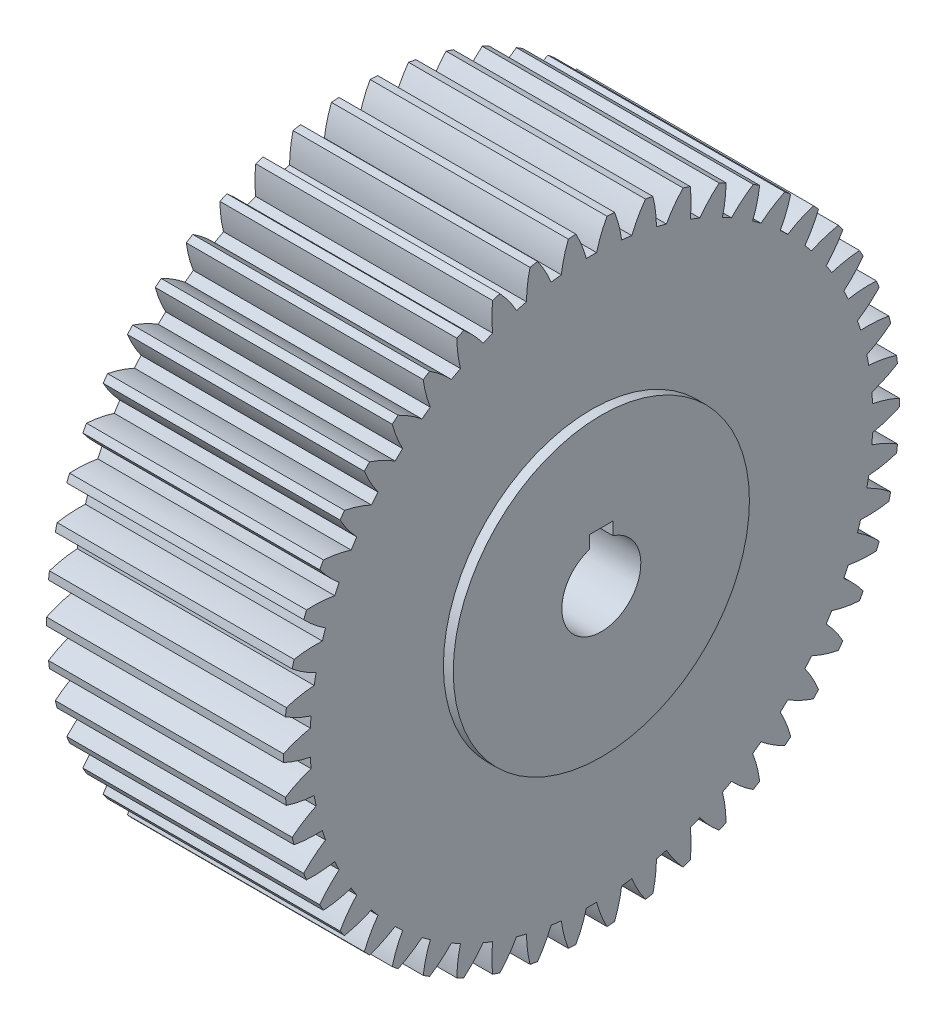
SolidWorks part; units mm, degrees
ref_plane "Plane1" through (0, 0, 0) normal (0, 0, 1) x (1, 0, 0)
ref_plane "Plane2" through (0, 0, 0) normal (0, 1, 0) x (1, 0, 0)
ref_plane "Plane3" through (0, 0, 0) normal (1, 0, 0) x (0, 0, -1)
other "Configuration Table"
sketch "HoldingSke" plane through (0, 0, 0) normal (0, 1, 0) x (1, 0, 0)
  line L0 (0, 0) -> (0.2143, -0.2553)
  line L1 (-15, 0) -> (100, 0) construction
  line L2 (0, 0) -> (-2.1039, 2.3779)
  line L3 (0, 0) -> (-11.863, 4.5341)
  line L4 (0, 0) -> (5.5511, 6.6156)
  line L5 (0, 0) -> (-60.9019, -22.7146)
  line L6 (0, 0) -> (-49.7378, -33.5582)
  line L7 (-2.1039, 2.3779) -> (11.8873, 65.8543)
  line L8 (-76.2, 54.61) -> (-73.4, 54.61)
  line L9 (-71.009, 38.7566) -> (-53.1078, 45.2721)
  line L10 (-76.2, 71.12) -> (104.1128, 71.12)
  line L11 (0, 0) -> (-60, 0)
  line L12 (-76.2, 101.6) -> (-76.093, 101.6)
  line L13 (24.9733, 27.94) -> (52.9518, 28.4284)
  line L14 (24.9733, 27.94) -> (24.9743, 27.94)
  line L15 (24.9733, 27.94) -> (100.4006, 29.5858)
  line L16 (-63.627, -3) -> (-12.827, -3)
  circle A0 centre (0, 0) radius 10
  circle A1 centre (0, 0) radius 37.5
  circle A2 centre (0, 0) radius 37.5
  circle A3 centre (0, 0) radius 10
  dimension "MHD" = 75
  dimension "Hub_dia" = 75
  dimension "Bore" = 20
  dimension "MBD" = 20
  dimension "Num_teeth" = 50
  dimension "Pitch" = 0.3333
  dimension "Overall_len" = 65
  dimension "Show_teeth" = 50
  dimension "Thickness" = 60
  dimension "OAL" = 65.0001
  dimension "T_dim" = 2.8
  dimension "Ap" = 20
  dimension "H" = 19.05
  dimension "Pitch_radius" = 180.3128
  dimension "Width" = 60
  dimension "Backlash" = 0.107
  dimension "Addendum_fac" = 1
  dimension "Dedendum_fac" = 1.25
  dimension "Clearance_fac" = 0.25
  dimension "Dedendum_add" = 0.001
  dimension "Module" = 3
sketch "BasProSke" plane through (0, 0, 0) normal (0, 1, 0) x (1, 0, 0)
  line L0 (-10, 0) -> (60, 0) construction
  line L1 (0, 0) -> (0, 78)
  line L2 (0, 0) -> (60, 0)
  line L3 (60, 0) -> (60, 78)
  line L4 (60, 78) -> (0, 78)
  dimension "Thickness" = 60
  dimension "Diameter" = 156
revolve "Base-Revolve" add sketch "BasProSke" angle 360 about L0
sketch "TooCutSke" plane through (0, 0, 0) normal (1, 0, 0) x (0, 0, -1)
  line L1 (0, 0) -> (0, 107) construction
  line L2 (0, 0) -> (-2.543, 74.9569) construction
  line L3 (0, 0) -> (-9.4146, 149.6414) construction
  line L4 (-2.543, 74.9569) -> (-4.7073, 74.8207) construction
  arc A0 (1.3019, 71.2371) -> (-1.3019, 71.2371) centre (0, 0) ccw
  arc A1 (3.9487, 77.9254) -> (-3.9487, 77.9254) centre (0, 0) ccw
  circle A2 centre (0, 0) radius 75 construction
  circle A3 centre (0, 0) radius 70.4769 construction
  arc A4 (-1.3019, 71.2371) -> (-3.9487, 77.9254) centre (-30.3193, 63.6219) ccw
  arc A5 (3.9487, 77.9254) -> (1.3019, 71.2371) centre (30.3193, 63.6219) ccw
  dimension "Root_dia" = 142.498
  dimension "Overcut_dia" = 156.0508
  dimension "Pitch_dia" = 150
  dimension "Base_dia" = 140.9539
  dimension "Flank_rad" = 30
  dimension "Half_ang" = 3.6
  dimension "Half_CT" = 2.1686
extrude "ToothCut" cut sketch "TooCutSke" along normal through all
fillet "Breaks" [suppressed] radius 0.06
fillet "RootFillets" [suppressed] radius 0.751
pattern_circular "TeethCuts" count 50 every 7.2 about axis through (-10, 0, 0) along (1, 0, 0) of "ToothCut", "RootFillets", "Breaks"
sketch "HubNeaOneSke" plane through (0, 0, 0) normal (-1, 0, 0) x (0, 0, 1)
  circle A0 centre (0, 0) radius 37.5
  dimension "Diameter" = 75
extrude "HubNearOne" [suppressed] add sketch "HubNeaOneSke" along normal blind 5.0001
sketch "HubNeaBotSke" plane through (0, 0, 0) normal (-1, 0, 0) x (0, 0, 1)
  circle A0 centre (0, 0) radius 37.5
  dimension "Diameter" = 75
extrude "HubNearBoth" add sketch "HubNeaBotSke" along normal blind 2.5
ref_plane "FarPln" through (60, 0, 0) normal (1, 0, 0) x (0, 0, -1)
sketch "HubFarSke" plane through (60, 0, 0) normal (1, 0, 0) x (0, 0, -1)
  circle A0 centre (0, 0) radius 37.5
  dimension "Diameter" = 75
extrude "HubFar" add sketch "HubFarSke" along normal blind 2.5
sketch "BorSke" plane through (0, 0, 0) normal (1, 0, 0) x (0, 0, -1)
  circle A0 centre (0, 0) radius 10
  dimension "Diameter" = 20
extrude "Bore" cut sketch "BorSke" along normal mid plane 130.0001
sketch "KeySke" plane through (0, 0, 0) normal (1, 0, 0) x (0, 0, -1)
  line L0 (-3, 0) -> (-3, 12.8)
  line L1 (-3, 12.8) -> (3, 12.8)
  line L2 (3, 12.8) -> (3, 0)
  line L3 (0, 0) -> (0, 34) construction
  line L4 (-3, 0) -> (3, 0)
  dimension "Offset" = 12.8
extrude "Keyway" cut sketch "KeySke" along normal mid plane 130.0001
pattern_circular "Keyway2" [suppressed] count 2 every 90 about axis through (-10, 0, 0) along (1, 0, 0)
equation "' \"Module@HoldingSke\" = 6.35"
equation "' \"Num_teeth@HoldingSke\" = 12"
equation "' \"Ap@HoldingSke\" =  20"
equation "' \"Ap@HoldingSke\" = 20"
equation "' \"Width@HoldingSke\" = 0.5 * 25.4"
equation "' \"Hub_dia@HoldingSke\"= 1 * 25.4"
equation "' \"Hub_dia@HoldingSke\" = 1 * 25.4"
equation "' \"Overall_len@HoldingSke\" = 1.0 * 25.4"
equation "' \"Bore@HoldingSke\" = 0.75 * 25.4"
equation "' \"T_dim@HoldingSke\" = 0.1 * 25.4"
equation "' \"Width@KeySke\" = 0.25 * 25.4"
equation "' \"Show_teeth@HoldingSke\" = 13"
equation "' \"Backlash@HoldingSke\" = 0.009 * 25.4"
equation "' \"Addendum_fac@HoldingSke\" = 1.0"
equation "' \"Dedendum_fac@HoldingSke\" = 1.25"
equation "' \"Dedendum_add@HoldingSke\" = 0.00005 * 25.4"
equation "' \"Clearance_fac@HoldingSke\" = 0.25"
equation "\"Pitch@HoldingSke\" = 1 / \"Module@HoldingSke\""
equation "\"Overcut_dia@TooCutSke\" = (\"Num_teeth@HoldingSke\" + 2 * \"Addendum_fac@HoldingSke\") / \"Pitch@HoldingSke\" + 0.002 * 25.4"
equation "\"Pitch_dia@TooCutSke\" = \"Num_teeth@HoldingSke\" / \"Pitch@HoldingSke\""
equation "\"Base_dia@TooCutSke\" = \"Num_teeth@HoldingSke\" / \"Pitch@HoldingSke\" * cos((\"Ap@HoldingSke\"  * 3.14159265 / 180))"
equation "\"Root_dia@TooCutSke\" = (\"Num_teeth@HoldingSke\" + 2) / \"Pitch@HoldingSke\" - 2 * (\"Addendum_fac@HoldingSke\" + \"Dedendum_fac@HoldingSke\") / \"Pitch@HoldingSke\" - \"Dedendum_add@HoldingSke\" * 2"
equation "\"Half_ang@TooCutSke\" = 180 / \"Num_teeth@HoldingSke\""
equation "\"Half_CT@TooCutSke\" = \"Num_teeth@HoldingSke\" / \"Pitch@HoldingSke\" * sin((3.14159265 / 2 / \"Num_teeth@HoldingSke\")) / 2 - 7 * \"Backlash@HoldingSke\" / 4"
equation "\"Flank_rad@TooCutSke\" = \"Num_teeth@HoldingSke\" / \"Pitch@HoldingSke\" / 5"
equation "\"Radius@RootFillets\" = \"Clearance_fac@HoldingSke\" / \"Pitch@HoldingSke\" + \"Dedendum_add@HoldingSke\""
equation "\"Break_rad@Breaks\" = 0.02 / \"Pitch@HoldingSke\""
equation "\"Thickness@HoldingSke\" = \"Width@HoldingSke\""
equation "\"OAL@HoldingSke\" = \"Thickness@HoldingSke\""
equation "\"MHD@HoldingSke\" = (\"Num_teeth@HoldingSke\" + 2) / \"Pitch@HoldingSke\" - 2 * (\"Addendum_fac@HoldingSke\" + \"Dedendum_fac@HoldingSke\")  / \"Pitch@HoldingSke\" - \"Dedendum_add@HoldingSke\" * 2"
equation "\"MBD@HoldingSke\" = (\"Num_teeth@HoldingSke\" + 2) / \"Pitch@HoldingSke\" - 2 * (\"Addendum_fac@HoldingSke\" + \"Dedendum_fac@HoldingSke\")  / \"Pitch@HoldingSke\" - \"Dedendum_add@HoldingSke\" * 2 - 0.002 * 25.4"
equation "\"MHD@HoldingSke\" = ((sgn( \"MHD@HoldingSke\" - \"Hub_dia@HoldingSke\" )-1)*( \"MHD@HoldingSke\" - \"Hub_dia@HoldingSke\" ))/-2+ \"Hub_dia@HoldingSke\""
equation "\"MBD@HoldingSke\" = ((sgn( \"MBD@HoldingSke\" - \"Bore@HoldingSke\" )-1)*( \"MBD@HoldingSke\" - \"Bore@HoldingSke\" ))/-2+ \"Bore@HoldingSke\""
equation "\"OAL@HoldingSke\" = ((sgn( \"OAL@HoldingSke\" - \"Overall_len@HoldingSke\" )+1)*( \"OAL@HoldingSke\" - \"Overall_len@HoldingSke\" ))/2 + \"Overall_len@HoldingSke\" + 0.000002 * 25.4"
equation "\"Num_teeth@TeethCuts\" = int( \"Show_teeth@HoldingSke\" ) + 1"
equation "\"Num_teeth@TeethCuts\" = ((sgn( \"Num_teeth@TeethCuts\" - \"Num_teeth@HoldingSke\" )-1)*( \"Num_teeth@TeethCuts\" - \"Num_teeth@HoldingSke\" ))/-2+ \"Num_teeth@HoldingSke\""
equation "\"Num_teeth@TeethCuts\" = ((sgn( \"Num_teeth@TeethCuts\" - 2.0)+1)*( \"Num_teeth@TeethCuts\" - 2.0))/2 +2.0"
equation "\"Angle@TeethCuts\" = 360.0 / \"Num_teeth@HoldingSke\""
equation "\"Diameter@BasProSke\" = (\"Num_teeth@HoldingSke\" + 2 * \"Addendum_fac@HoldingSke\") / \"Pitch@HoldingSke\""
equation "\"Thickness@BasProSke\"  = \"Thickness@HoldingSke\""
equation "' \"Fillet_rad@BasProSke\" =  \"Thickness@HoldingSke\" * 0.05"
equation "' \"Fillet_rad@BasProSke\" = \"Thickness@HoldingSke\" * 0.05"
equation "\"MHD@HoldingSke\" = ((sgn( \"MHD@HoldingSke\" - \"Root_dia@TooCutSke\" )-1)*( \"MHD@HoldingSke\" - \"Root_dia@TooCutSke\" ))/-2+ \"Root_dia@TooCutSke\""
equation "\"Diameter@HubNeaOneSke\" = \"MHD@HoldingSke\""
equation "\"Length@HubNearOne\" = \"OAL@HoldingSke\" - \"Thickness@BasProSke\""
equation "\"Diameter@HubNeaBotSke\" = \"MHD@HoldingSke\""
equation "\"Length@HubNearBoth\" = ( \"OAL@HoldingSke\" - \"Thickness@BasProSke\" ) / 2.0"
equation "\"Thickness@FarPln\" = \"Thickness@BasProSke\""
equation "\"Diameter@HubFarSke\" = \"MHD@HoldingSke\""
equation "\"Length@HubFar\" = ( \"OAL@HoldingSke\" - \"Thickness@BasProSke\" ) / 2.0"
equation "\"Diameter@BorSke\" = \"MBD@HoldingSke\""
equation "\"D1@Bore\" = \"OAL@HoldingSke\" * 2.0"
equation "\"D1@Keyway\" = \"OAL@HoldingSke\" * 2.0"
equation "\"Offset@KeySke\" = \"T_dim@HoldingSke\" + \"MBD@HoldingSke\" / 2.0"
